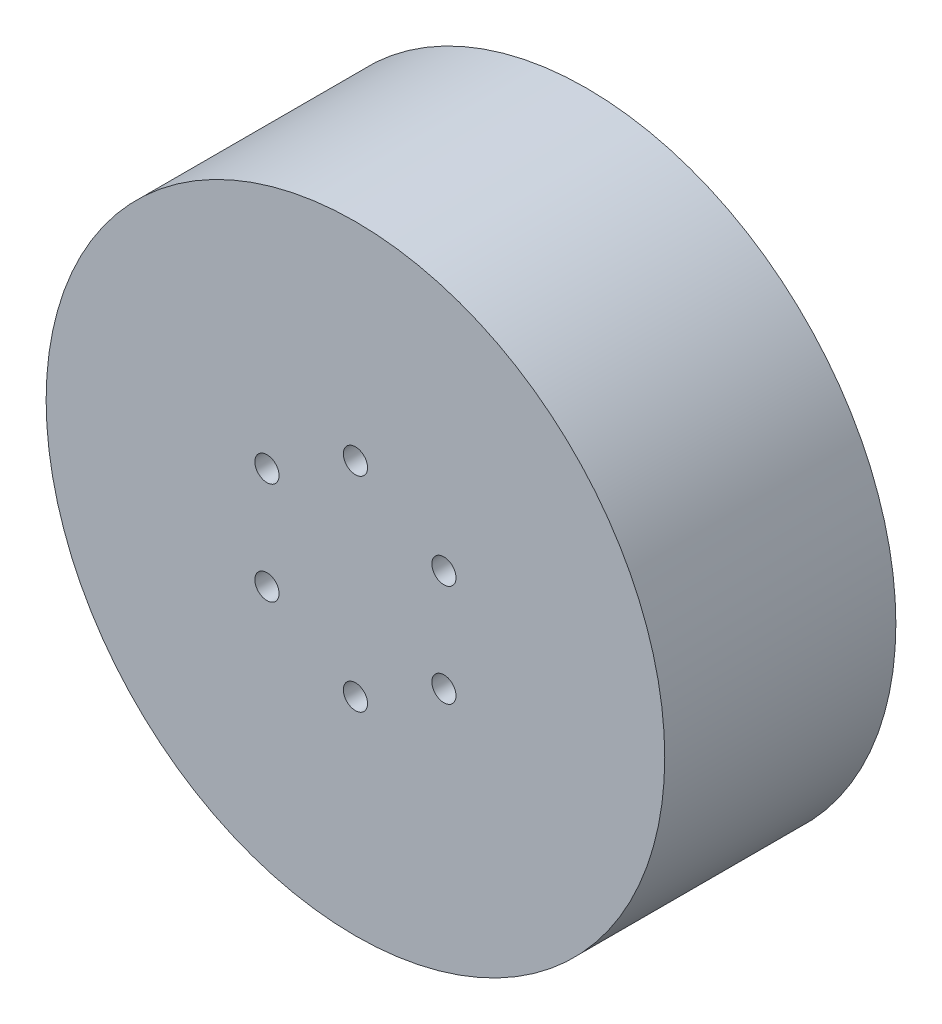
SolidWorks part; units mm, degrees
material "4140 Steel"
ref_plane "Front Plane" through (0, 0, 0) normal (0, 0, 1) x (1, 0, 0)
ref_plane "Top Plane" through (0, 0, 0) normal (0, 1, 0) x (1, 0, 0)
ref_plane "Right Plane" through (0, 0, 0) normal (1, 0, 0) x (0, 0, -1)
sketch "Sketch1" plane through (0, 0, 0) normal (0, 0, 1) x (1, 0, 0)
  circle A0 centre (0, 0) radius 113.538
  dimension "D1" = 227.076
extrude "Boss-Extrude1" add sketch "Sketch1" against normal blind 84.836
sketch "Sketch2" plane through (0, 0, 0) normal (0, 0, 1) x (1, 0, 0)
  line L0 (0, 0) -> (0, -114.046) construction
  line L1 (0, -114.046) -> (0, 114.046) construction
  line L2 (0, 114.046) -> (0, 0) construction
  line L3 (0, 0) -> (-114.046, 0) construction
  line L4 (-114.046, 0) -> (114.046, 0) construction
  circle A0 centre (0, 37.5) radius 4.445
  circle A1 centre (0, 0) radius 33.147
  circle A2 centre (32.476, 18.75) radius 4.445
  circle A3 centre (0, 0) radius 33.147
  circle A4 centre (32.476, -18.75) radius 4.445
  circle A5 centre (0, 0) radius 33.147
  circle A6 centre (0, -37.5) radius 4.445
  circle A7 centre (0, 0) radius 33.147
  circle A8 centre (-32.476, -18.75) radius 4.445
  circle A9 centre (0, 0) radius 33.147
  circle A10 centre (-32.476, 18.75) radius 4.445
  circle A11 centre (0, 0) radius 33.147
  point P7 (0, 37.5)
  point P27 (0, 0)
  dimension "D1" = 37.5
  dimension "D3" = 8.89
  dimension "D2" = 0
  dimension "D4" = 6
extrude "Cut-Extrude1" cut sketch "Sketch2" against normal through all both and the other way through all contours A10 | A0 | A2 | A4 | A6 | A8
sketch "Sketch3" plane through (0, 0, 0) normal (0, 0, 1) x (1, 0, 0)
  circle A0 centre (0, 0) radius 37.5
  point P0 (0, 0)
  dimension "D1" = 75
sketch "Sketch4" plane through (0, 0, -84.836) normal (0, 0, -1) x (-1, 0, 0)
  circle A0 centre (0, 0) radius 23.8412
extrude "Boss-Extrude2" add sketch "Sketch4" along normal blind 13.97
